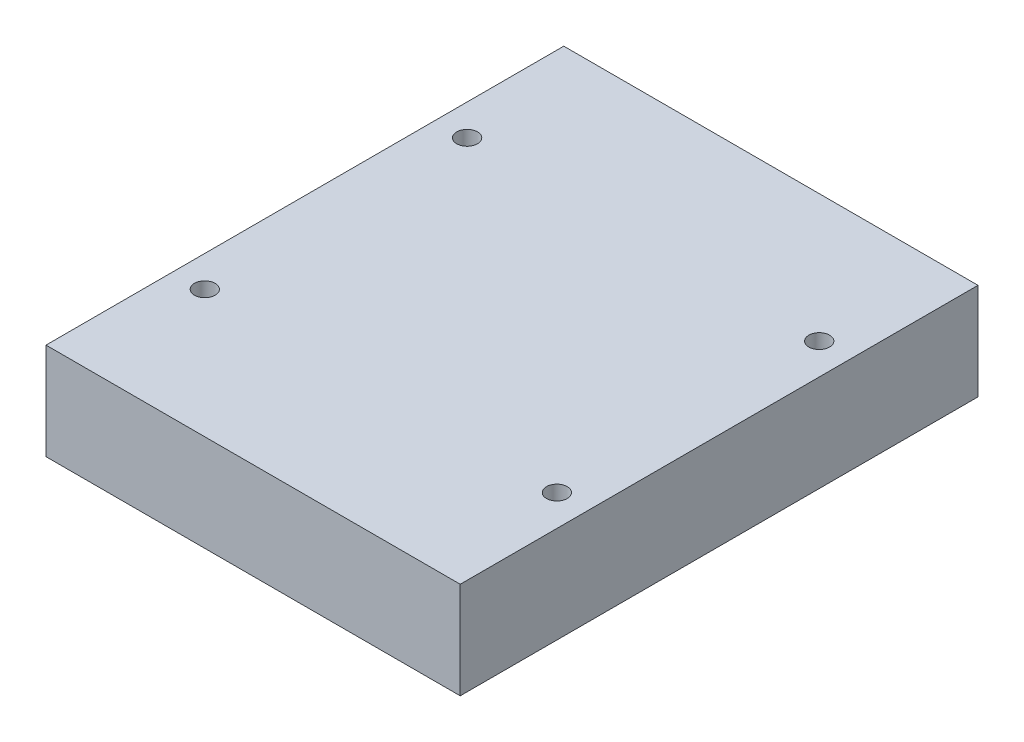
SolidWorks part; units mm, degrees
ref_plane "Front Plane" through (0, 0, 0) normal (0, 0, 1) x (1, 0, 0)
ref_plane "Top Plane" through (0, 0, 0) normal (0, 1, 0) x (1, 0, 0)
ref_plane "Right Plane" through (0, 0, 0) normal (1, 0, 0) x (0, 0, -1)
sketch "Sketch1" plane through (0, 0, 0) normal (0, 1, 0) x (1, 0, 0)
  line L1 (-30, 37.5) -> (30, 37.5)
  line L2 (-30, 37.5) -> (-30, -37.5)
  line L3 (-30, -37.5) -> (30, -37.5)
  line L4 (30, 37.5) -> (30, -37.5)
  line L5 (-30, 37.5) -> (30, -37.5) construction
  line L6 (-30, -37.5) -> (30, 37.5) construction
  point P0 (0, 0)
  dimension "D1" = 60
  dimension "D2" = 75
extrude "Boss-Extrude1" add sketch "Sketch1" along normal blind 14
sketch "Sketch2" plane through (0, 14, 0) normal (0, 1, 0) x (1, 0, 0)
  line L1 (25.5, -19) -> (-25.5, -19) construction
  line L2 (25.5, -19) -> (25.5, 19) construction
  line L3 (25.5, 19) -> (-25.5, 19) construction
  line L4 (-25.5, -19) -> (-25.5, 19) construction
  line L5 (25.5, -19) -> (-25.5, 19) construction
  line L6 (25.5, 19) -> (-25.5, -19) construction
  circle A0 centre (-25.5, 19) radius 1.5
  circle A1 centre (25.5, 19) radius 1.5
  circle A2 centre (25.5, -19) radius 1.5
  circle A3 centre (-25.5, -19) radius 1.5
  point P8 (0, 0)
  dimension "D1" = 3
  dimension "D2" = 51
  dimension "D3" = 38
extrude "Cut-Extrude1" cut sketch "Sketch2" against normal blind 14
